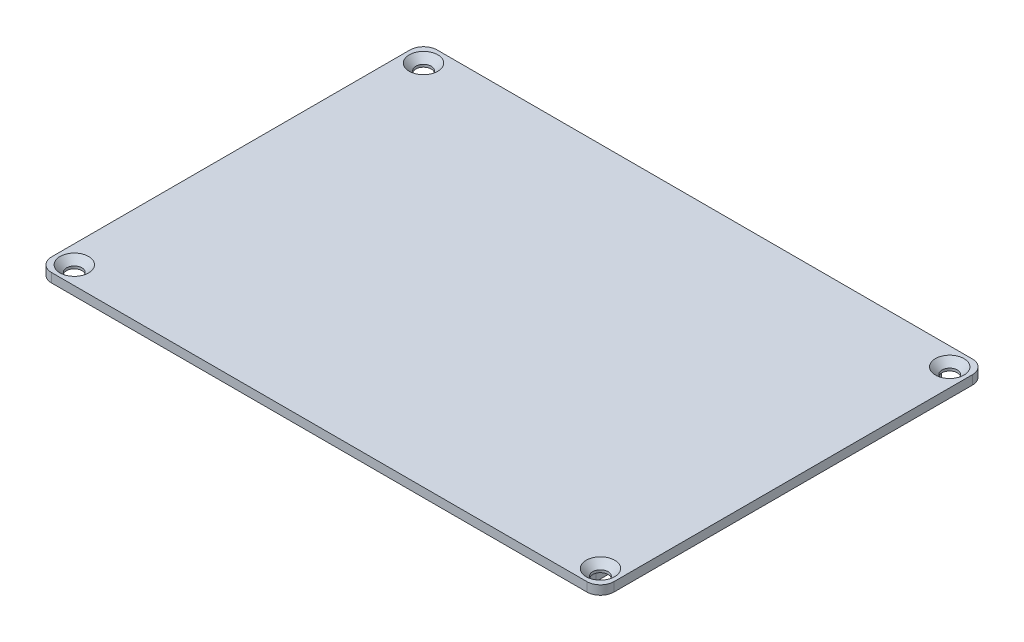
SolidWorks part; units mm, degrees
ref_plane "Ebene vorne" through (0, 0, 0) normal (0, 0, 1) x (1, 0, 0)
ref_plane "Ebene oben" through (0, 0, 0) normal (0, 1, 0) x (1, 0, 0)
ref_plane "Ebene rechts" through (0, 0, 0) normal (1, 0, 0) x (0, 0, -1)
sketch "Skizze1" plane through (0, 0, 0) normal (0, 1, 0) x (1, 0, 0)
  line L1 (0, 0) -> (112, 0)
  line L2 (0, 0) -> (0, 81)
  line L3 (0, 81) -> (112, 81)
  line L4 (112, 0) -> (112, 81)
  line L5 (2, 2) -> (110, 2)
  line L6 (2, 2) -> (2, 79)
  line L7 (2, 79) -> (110, 79)
  line L8 (110, 2) -> (110, 79)
  dimension "D1" = 112
  dimension "D2" = 81
  dimension "D3" = 2
  dimension "D4" = 2
  dimension "D5" = 2
  dimension "D6" = 2
extrude "Aufsatz-Linear austragen1" add sketch "Skizze1" along normal blind 2
sketch "Skizze2" plane through (0, 2, 0) normal (0, 1, 0) x (1, 0, 0)
  line L0 (0, 81) -> (0, 0) construction
  line L1 (-6, -2) -> (118, -2)
  line L2 (-6, -2) -> (-6, 83)
  line L3 (-6, 83) -> (118, 83)
  line L4 (118, -2) -> (118, 83)
  line L5 (112, 0) -> (112, 81) construction
  line L6 (112, 81) -> (0, 81) construction
  line L7 (0, 0) -> (112, 0) construction
  dimension "D1" = 6
  dimension "D2" = 6
  dimension "D3" = 2
  dimension "D4" = 2
extrude "Aufsatz-Linear austragen2" add sketch "Skizze2" along normal blind 2
fillet "Verrundung1" radius 3 8 edges at (118, 3, 2) (118, 3, -83) (-6, 3, -83) (-6, 3, 2) (0, 1, 0) (0, 1, -81) (112, 1, -81) (112, 1, 0)
hole_wizard "Formsenkung für M3 Linsensenkschraube mit Schlitz1" positions "Skizze3" profile "Skizze4" countersink size "M3" standard "DIN"
sketch "Skizze3" plane through (0, 4, 0) normal (0, 1, 0) x (1, 0, 0)
  line L1 (-2, 2) -> (114, 2) construction
  line L2 (-2, 2) -> (-2, 79) construction
  line L3 (-2, 79) -> (114, 79) construction
  line L4 (114, 2) -> (114, 79) construction
  line L5 (-6, 80) -> (-6, 1) construction
  line L6 (118, 1) -> (118, 80) construction
  line L7 (115, 83) -> (-3, 83) construction
  line L8 (-3, -2) -> (115, -2) construction
  point P0 (-2, 2)
  point P1 (114, 79)
  point P128 (-2, 79)
  point P129 (114, 2)
  dimension "D1" = 4
  dimension "D2" = 4
  dimension "D3" = 4
  dimension "D4" = 4
sketch "Skizze4" plane through (-2, 4, -2) normal (1, 0, 0) x (0, 0, 1)
  line L0 (0, 0) -> (0, 8.2715)
  line L1 (0, 8.2715) -> (1.7, 7.25)
  line L2 (1.7, 7.25) -> (1.7, 1.45)
  line L3 (1.7, 1.45) -> (3.15, 0)
  line L5 (3.15, 0) -> (0, 0)
  line L6 (-1.7, 1.45) -> (-3.15, 0) construction
  line L10 (0, 8.2715) -> (-1.7, 7.25) construction
  line L11 (0, -6.35) -> (0, 107.95) construction
  dimension "Bohrerdurchmesser" = 3.4
  dimension "Bohrungstiefe" = 7.25
  dimension "Senkdurchmesser (Oben)" = 6.3
  dimension "Senkwinkel (Oben)" = 90
  dimension "Spitzenwinkel" = 118
